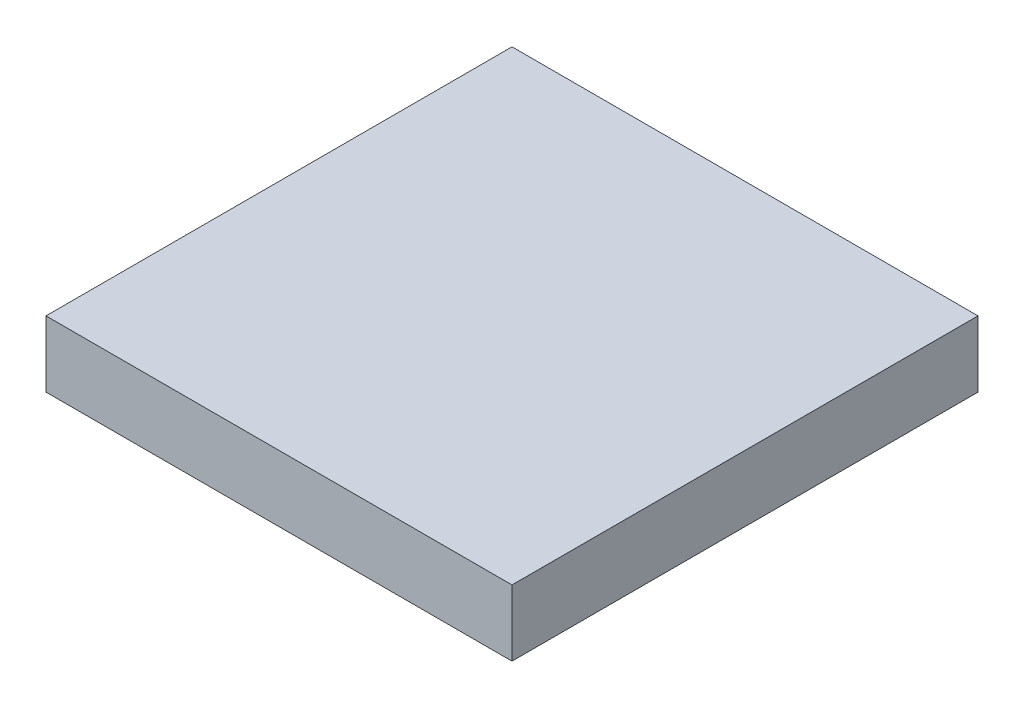
SolidWorks part; units mm, degrees
ref_plane "Alzado" through (0, 0, 0) normal (0, 0, 1) x (1, 0, 0)
ref_plane "Planta" through (0, 0, 0) normal (0, 1, 0) x (1, 0, 0)
ref_plane "Vista lateral" through (0, 0, 0) normal (1, 0, 0) x (0, 0, -1)
sketch "Croquis1" plane through (0, 0, 0) normal (0, 1, 0) x (1, 0, 0)
  line L1 (-19.05, 19.05) -> (19.05, 19.05)
  line L2 (-19.05, 19.05) -> (-19.05, -19.05)
  line L3 (-19.05, -19.05) -> (19.05, -19.05)
  line L4 (19.05, 19.05) -> (19.05, -19.05)
  line L5 (-19.05, 19.05) -> (19.05, -19.05) construction
  line L6 (-19.05, -19.05) -> (19.05, 19.05) construction
  point P0 (0, 0)
  dimension "D1" = 38.1
  dimension "D2" = 38.1
extrude "Saliente-Extruir1" add sketch "Croquis1" along normal blind 5.4
